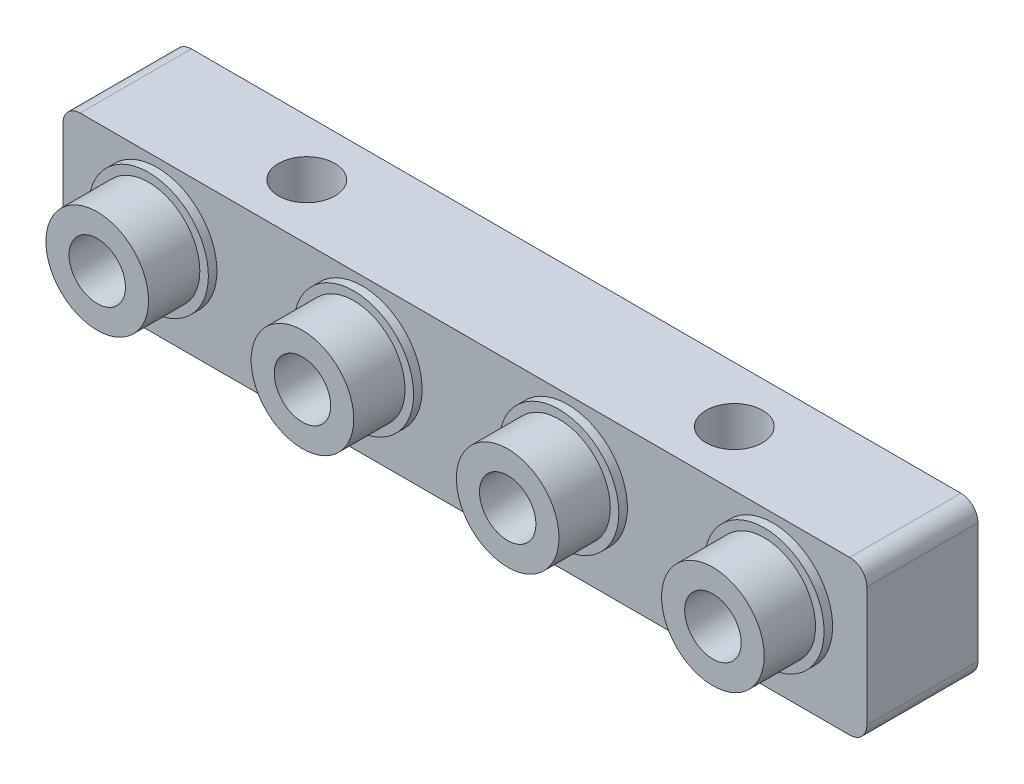
SolidWorks part; units mm, degrees
material "5052-H34"
ref_plane "正面" through (0, 0, 0) normal (0, 0, 1) x (1, 0, 0)
ref_plane "平面" through (0, 0, 0) normal (0, 1, 0) x (1, 0, 0)
ref_plane "右側面" through (0, 0, 0) normal (1, 0, 0) x (0, 0, -1)
sketch "ｽｹｯﾁ1" plane through (0, 0, 0) normal (0, 0, 1) x (1, 0, 0)
  line L1 (0, 0) -> (47, 0)
  line L2 (0, 0) -> (0, 9)
  line L3 (0, 9) -> (47, 9)
  line L4 (47, 0) -> (47, 9)
  dimension "D1" = 9
  dimension "D2" = 47
extrude "ﾎﾞｽ - 押し出し1" add sketch "ｽｹｯﾁ1" along normal blind 6.5
sketch "ｽｹｯﾁ2" plane through (0, 0, 6.5) normal (0, 0, 1) x (1, 0, 0)
  line L0 (47, 4.5) -> (0, 4.5) construction
  line L1 (47, 0) -> (47, 9) construction
  line L2 (0, 9) -> (0, 0) construction
  line L3 (47, 9) -> (0, 9) construction
  circle A0 centre (5.5, 5) radius 3
  circle A1 centre (17.5, 5) radius 3
  circle A2 centre (29.5, 5) radius 3
  circle A7 centre (5.5, 5) radius 5 construction
  circle A8 centre (17.5, 5) radius 5 construction
  circle A9 centre (29.5, 5) radius 5 construction
  circle A10 centre (41.5, 5) radius 3
  circle A11 centre (41.5, 5) radius 5 construction
  dimension "D1" = 6
  dimension "D5" = 5.5
  dimension "D6" = 10
  dimension "D2" = 5.5
  dimension "D3" = 4
  dimension "D4" = 4
extrude "ﾎﾞｽ - 押し出し2" add sketch "ｽｹｯﾁ2" along normal blind 3.5
sketch "ｽｹｯﾁ3" plane through (0, 0, 6.5) normal (0, 0, 1) x (1, 0, 0)
  circle A0 centre (5.5, 5) radius 3.5
  circle A1 centre (5.5, 5) radius 3 construction
  circle A2 centre (17.5, 5) radius 3.5
  circle A3 centre (29.5, 5) radius 3.5
  circle A4 centre (41.5, 5) radius 3.5
  dimension "D1" = 0.5
extrude "ﾎﾞｽ - 押し出し3" add sketch "ｽｹｯﾁ3" along normal blind 0.5
sketch "ｽｹｯﾁ4" plane through (0, 0, 10) normal (0, 0, 1) x (1, 0, 0)
  circle A0 centre (5.5, 5) radius 1.65
  circle A1 centre (17.5, 5) radius 1.65
  circle A2 centre (29.5, 5) radius 1.65
  circle A3 centre (41.5, 5) radius 1.65
  dimension "D1" = 3.3
extrude "ｶｯﾄ - 押し出し1" cut sketch "ｽｹｯﾁ4" against normal up to surface (10 mm away) up to face at (23.5, 4.5, 0)
sketch "ｽｹｯﾁ5" plane through (0, 9, 0) normal (0, 1, 0) x (1, 0, 0)
  line L0 (47, -3.25) -> (0, -3.25) construction
  line L1 (47, -6.5) -> (47, 0) construction
  line L2 (0, -6.5) -> (0, 0) construction
  line L3 (23.5, 0) -> (23.5, -6.5) construction
  line L4 (47, 0) -> (0, 0) construction
  line L5 (47, -6.5) -> (0, -6.5) construction
  circle A0 centre (11, -3.25) radius 1.65
  circle A1 centre (36, -3.25) radius 1.65
  dimension "D2" = 3.3
  dimension "D1" = 25
extrude "ｶｯﾄ - 押し出し2" cut sketch "ｽｹｯﾁ5" against normal up to surface (9 mm away) up to face at (23.5, 0, 3.25)
fillet "ﾌｨﾚｯﾄ1" radius 1 4 edges at (47, 0, 3.25) (47, 9, 3.25) (0, 0, 3.25) (0, 9, 3.25)
